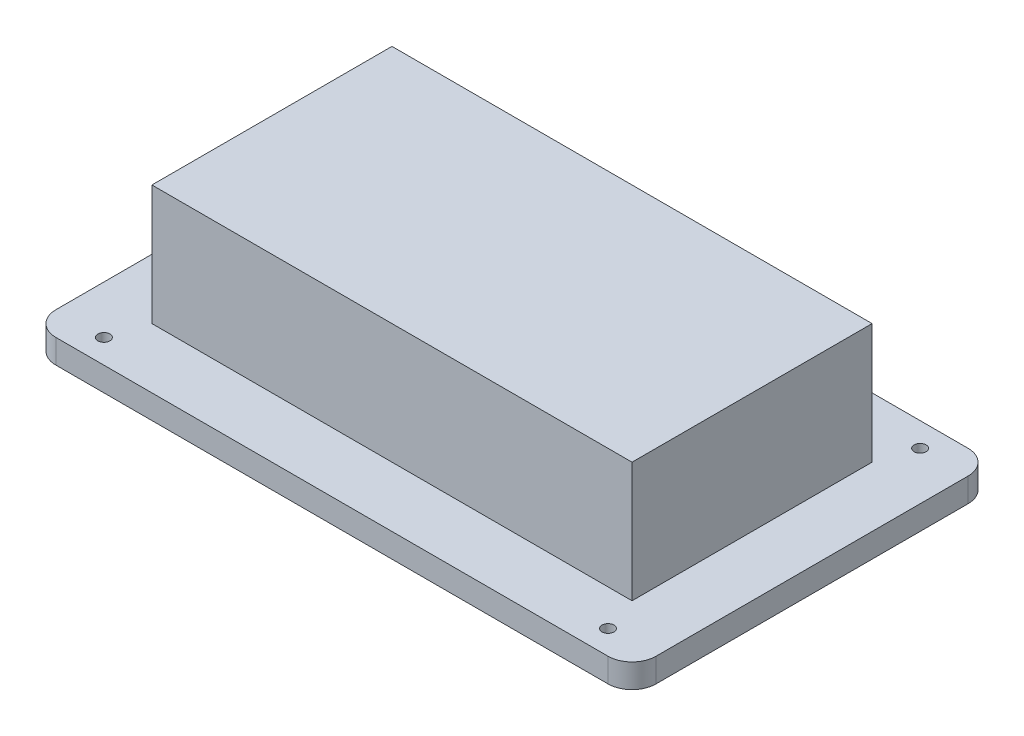
SolidWorks part; units mm, degrees
material "Q235-A"
ref_plane "前视基准面" through (0, 0, 0) normal (0, 0, 1) x (1, 0, 0)
ref_plane "上视基准面" through (0, 0, 0) normal (0, 1, 0) x (1, 0, 0)
ref_plane "右视基准面" through (0, 0, 0) normal (1, 0, 0) x (0, 0, -1)
sketch "草图1" plane through (0, 0, 0) normal (0, 1, 0) x (1, 0, 0)
  line L1 (-125, 75) -> (125, 75)
  line L2 (-125, 75) -> (-125, -75)
  line L3 (-125, -75) -> (125, -75)
  line L4 (125, 75) -> (125, -75)
  line L5 (-125, 75) -> (125, -75) construction
  line L6 (-125, -75) -> (125, 75) construction
  point P0 (0, 0)
  dimension "D1" = 250
  dimension "D2" = 150
extrude "凸台-拉伸1" add sketch "草图1" along normal blind 10
fillet "圆角1" radius 10 4 edges at (-125, 5, -75) (125, 5, -75) (125, 5, 75) (-125, 5, 75)
sketch "草图2" plane through (0, 10, 0) normal (0, 1, 0) x (1, 0, 0)
  line L1 (-100, -50) -> (100, -50)
  line L2 (-100, -50) -> (-100, 50)
  line L3 (-100, 50) -> (100, 50)
  line L4 (100, -50) -> (100, 50)
  line L5 (-100, -50) -> (100, 50) construction
  line L6 (-100, 50) -> (100, -50) construction
  point P0 (0, 0)
  dimension "D1" = 200
  dimension "D2" = 100
extrude "凸台-拉伸2" add sketch "草图2" along normal blind 50
sketch "草图3" plane through (0, 10, 0) normal (0, 1, 0) x (1, 0, 0)
  line L0 (0, 0) -> (0, 65) construction
  line L2 (105, 65) -> (-105, 65) construction
  line L3 (0, 0) -> (-21.8719, 0) construction
  line L4 (105, -65) -> (-105, -65) construction
  point P3 (105, 65)
  point P4 (-105, 65)
  point P6 (105, -65)
  point P8 (-105, -65)
  dimension "D1" = 65
  dimension "D2" = 105
hole_wizard "M6 螺纹孔1" positions "草图3" profile "草图4" tap size "M6" standard "GB"
sketch "草图4" plane through (-105, 10, 65) normal (1, 0, 0) x (0, 0, 1)
  line L0 (0, 0) -> (0, 16.5022)
  line L1 (0, 16.5022) -> (2.5, 15)
  line L2 (2.5, 15) -> (2.5, 0)
  line L5 (2.5, 0) -> (0, 0)
  line L10 (0, 16.5022) -> (-2.5, 15) construction
  line L11 (0, -6.35) -> (0, 107.95) construction
  dimension "螺纹孔钻头直径" = 5
  dimension "螺纹孔钻头深度" = 15
  dimension "导头角度" = 118
cosmetic thread "孔螺纹线1" parameters "D1"=12, "D2"=6
cosmetic thread "孔螺纹线2" parameters "D1"=12, "D2"=6
cosmetic thread "孔螺纹线3" parameters "D1"=12, "D2"=6
cosmetic thread "孔螺纹线4" parameters "D1"=12, "D2"=6
